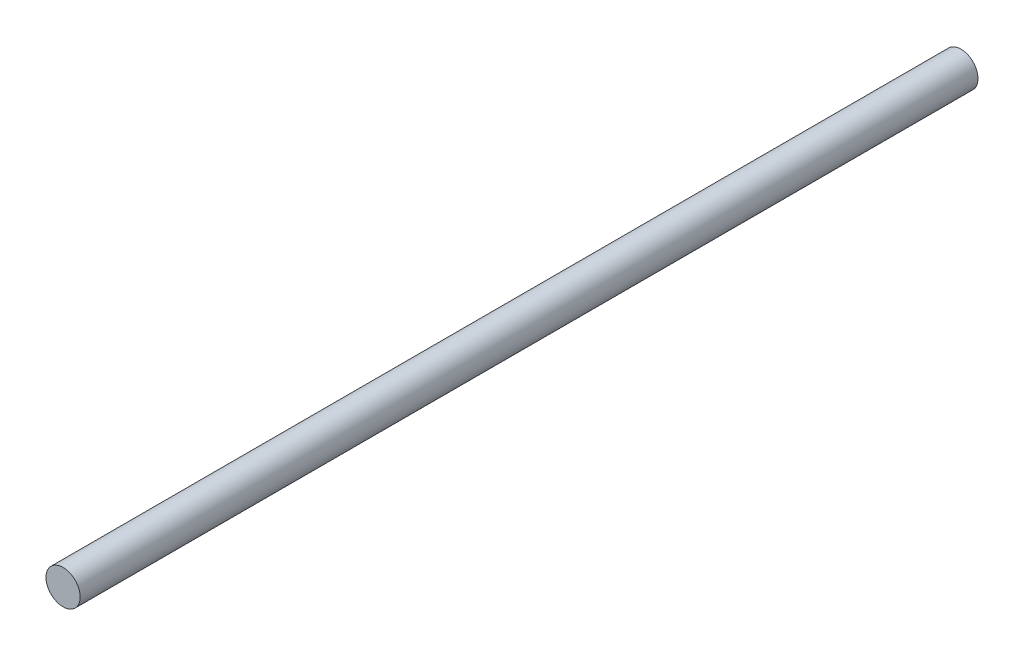
SolidWorks part; units mm, degrees
ref_plane "Front Plane" through (0, 0, 0) normal (0, 0, 1) x (1, 0, 0)
ref_plane "Top Plane" through (0, 0, 0) normal (0, 1, 0) x (1, 0, 0)
ref_plane "Right Plane" through (0, 0, 0) normal (1, 0, 0) x (0, 0, -1)
sketch "Sketch1" plane through (0, 0, 0) normal (0, 0, 1) x (1, 0, 0)
  circle A0 centre (0, 0) radius 4
  dimension "D1" = 8
extrude "Boss-Extrude1" add sketch "Sketch1" against normal blind 210
